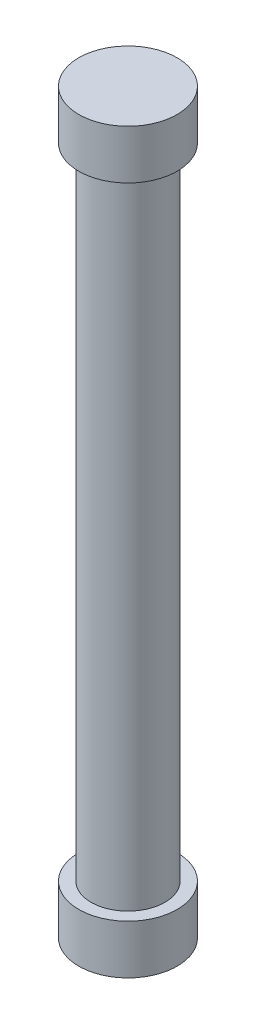
SolidWorks part; units mm, degrees
ref_plane "Front Plane" through (0, 0, 0) normal (0, 0, 1) x (1, 0, 0)
ref_plane "Top Plane" through (0, 0, 0) normal (0, 1, 0) x (1, 0, 0)
ref_plane "Right Plane" through (0, 0, 0) normal (1, 0, 0) x (0, 0, -1)
sketch "Sketch1" plane through (0, 0, 0) normal (0, 0, 1) x (1, 0, 0)
  line L1 (0, -30) -> (-2, -30)
  line L2 (-2, -30) -> (-2, -28)
  line L3 (-2, -28) -> (-1.5, -28)
  line L4 (-1.5, -28) -> (-1.5, -2)
  line L5 (-1.5, -2) -> (-2, -2)
  line L6 (-2, -2) -> (-2, 0)
  line L7 (-2, 0) -> (0, 0)
  line L9 (0, 0) -> (0, -30)
  dimension "D1" = 30
  dimension "D2" = 1.5
  dimension "D3" = 2
  dimension "D4" = 2
  dimension "D5" = 2
  dimension "D6" = 2
revolve "Revolve1" add sketch "Sketch1" angle 360 about L9
